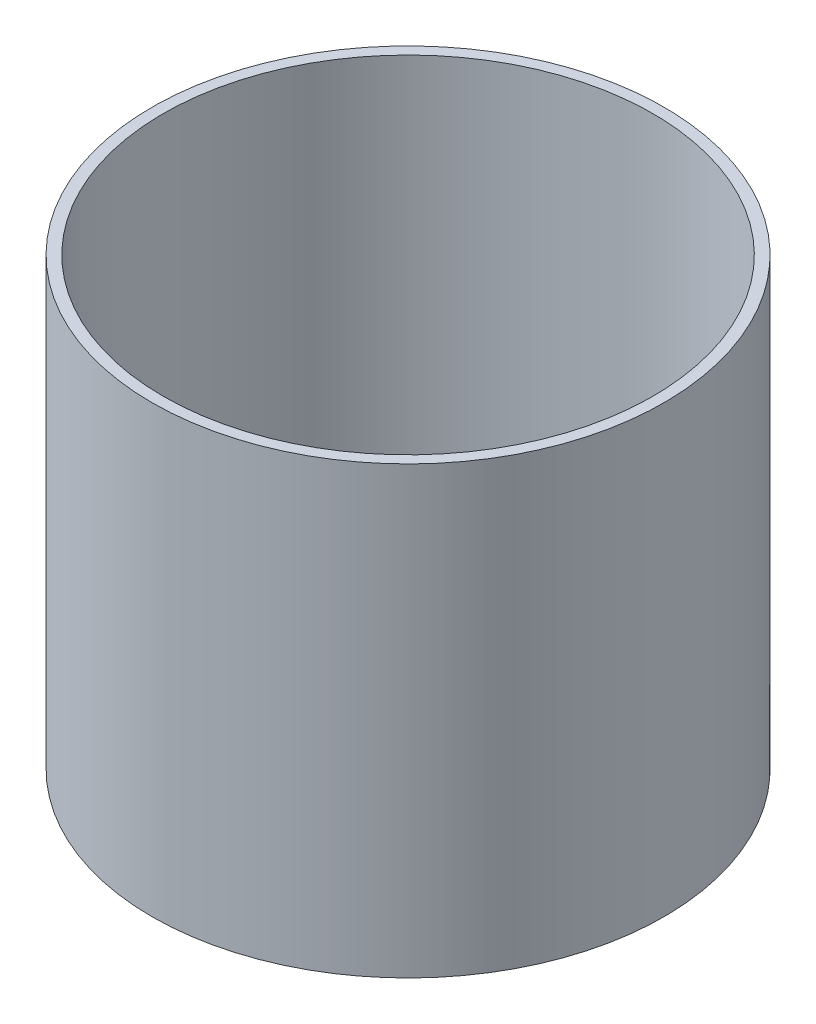
SolidWorks part; units mm, degrees
ref_plane "Front Plane" through (0, 0, 0) normal (0, 0, 1) x (1, 0, 0)
ref_plane "Top Plane" through (0, 0, 0) normal (0, 1, 0) x (1, 0, 0)
ref_plane "Right Plane" through (0, 0, 0) normal (1, 0, 0) x (0, 0, -1)
sketch "Sketch1" plane through (0, 0, 0) normal (0, 1, 0) x (1, 0, 0)
  circle A0 centre (0, 0) radius 22
  circle A1 centre (0, 0) radius 23
  dimension "D1" = 44
  dimension "D2" = 46
extrude "Boss-Extrude1" add sketch "Sketch1" along normal blind 40
